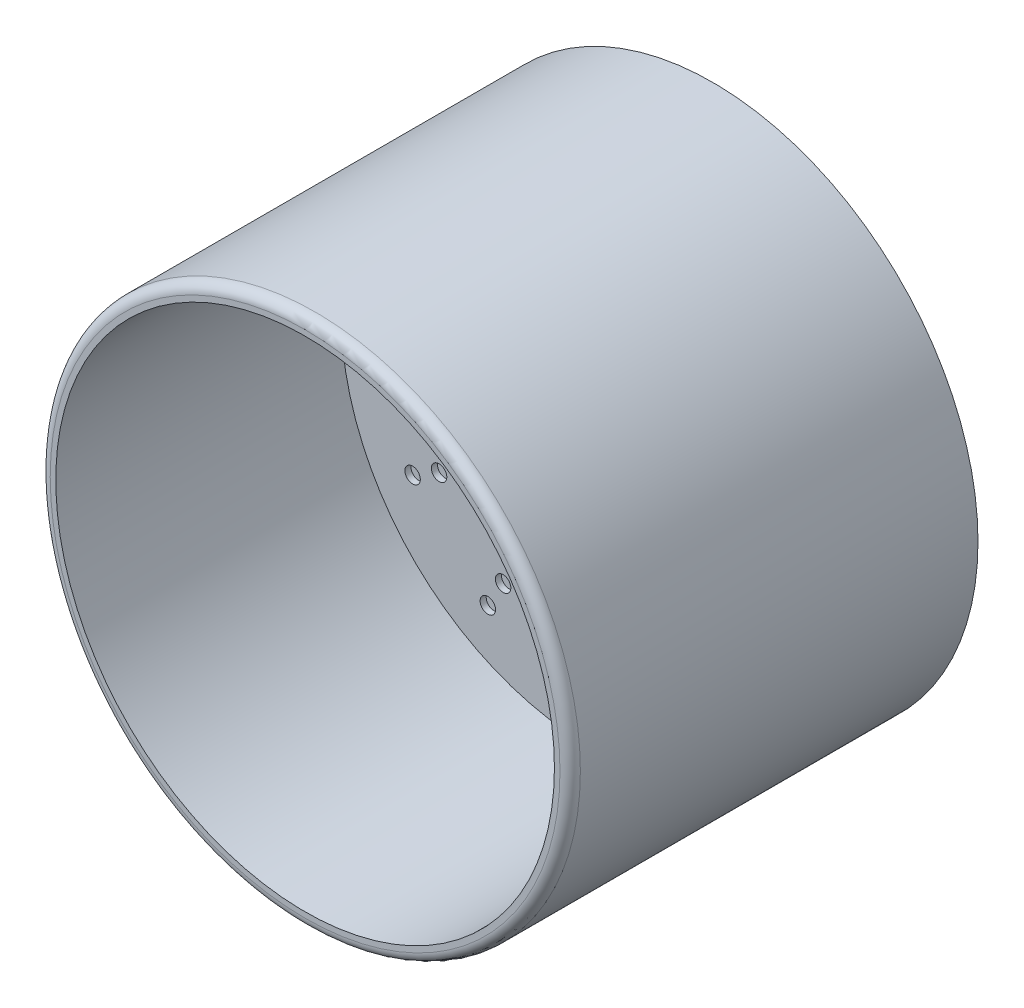
SolidWorks part; units mm, degrees
material "1023 Carbon Steel Sheet (SS)"
ref_plane "Front Plane" through (0, 0, 0) normal (0, 0, 1) x (1, 0, 0)
ref_plane "Top Plane" through (0, 0, 0) normal (0, 1, 0) x (1, 0, 0)
ref_plane "Right Plane" through (0, 0, 0) normal (1, 0, 0) x (0, 0, -1)
sketch "Sketch1" plane through (0, 0, 0) normal (0, 0, 1) x (1, 0, 0)
  circle A0 centre (0, 0) radius 13
extrude "Boss-Extrude1" add sketch "Sketch1" along normal blind 20
sketch "Sketch2" plane through (0, 0, 20) normal (0, 0, 1) x (1, 0, 0)
  circle A0 centre (0, 0) radius 12.2278
extrude "Cut-Extrude1" cut sketch "Sketch2" against normal blind 14
sketch "Sketch3" plane through (0, 0, 6) normal (0, 0, 1) x (1, 0, 0)
  circle A0 centre (0, 10.078) radius 0.3784
  circle A1 centre (0, 8.578) radius 0.3784
  circle A2 centre (0, 7.078) radius 0.3784
  circle A3 centre (0, 5.578) radius 0.3784
  circle A4 centre (0, 4.078) radius 0.3784
  circle A5 centre (0, 2.578) radius 0.3784
  circle A6 centre (5.039, 8.7278) radius 0.3784
  circle A7 centre (4.289, 7.4287) radius 0.3784
  circle A8 centre (3.539, 6.1297) radius 0.3784
  circle A9 centre (2.789, 4.8307) radius 0.3784
  circle A10 centre (2.039, 3.5316) radius 0.3784
  circle A11 centre (1.289, 2.2326) radius 0.3784
  circle A12 centre (8.7278, 5.039) radius 0.3784
  circle A13 centre (7.4287, 4.289) radius 0.3784
  circle A14 centre (6.1297, 3.539) radius 0.3784
  circle A15 centre (4.8307, 2.789) radius 0.3784
  circle A16 centre (3.5316, 2.039) radius 0.3784
  circle A17 centre (2.2326, 1.289) radius 0.3784
  circle A18 centre (10.078, 0) radius 0.3784
  circle A19 centre (8.578, 0) radius 0.3784
  circle A20 centre (7.078, 0) radius 0.3784
  circle A21 centre (5.578, 0) radius 0.3784
  circle A22 centre (4.078, 0) radius 0.3784
  circle A23 centre (2.578, 0) radius 0.3784
  circle A24 centre (8.7278, -5.039) radius 0.3784
  circle A25 centre (7.4287, -4.289) radius 0.3784
  circle A26 centre (6.1297, -3.539) radius 0.3784
  circle A27 centre (4.8307, -2.789) radius 0.3784
  circle A28 centre (3.5316, -2.039) radius 0.3784
  circle A29 centre (2.2326, -1.289) radius 0.3784
  circle A30 centre (5.039, -8.7278) radius 0.3784
  circle A31 centre (4.289, -7.4287) radius 0.3784
  circle A32 centre (3.539, -6.1297) radius 0.3784
  circle A33 centre (2.789, -4.8307) radius 0.3784
  circle A34 centre (2.039, -3.5316) radius 0.3784
  circle A35 centre (1.289, -2.2326) radius 0.3784
  circle A36 centre (0, -10.078) radius 0.3784
  circle A37 centre (0, -8.578) radius 0.3784
  circle A38 centre (0, -7.078) radius 0.3784
  circle A39 centre (0, -5.578) radius 0.3784
  circle A40 centre (0, -4.078) radius 0.3784
  circle A41 centre (0, -2.578) radius 0.3784
  circle A42 centre (-5.039, -8.7278) radius 0.3784
  circle A43 centre (-4.289, -7.4287) radius 0.3784
  circle A44 centre (-3.539, -6.1297) radius 0.3784
  circle A45 centre (-2.789, -4.8307) radius 0.3784
  circle A46 centre (-2.039, -3.5316) radius 0.3784
  circle A47 centre (-1.289, -2.2326) radius 0.3784
  circle A48 centre (-8.7278, -5.039) radius 0.3784
  circle A49 centre (-7.4287, -4.289) radius 0.3784
  circle A50 centre (-6.1297, -3.539) radius 0.3784
  circle A51 centre (-4.8307, -2.789) radius 0.3784
  circle A52 centre (-3.5316, -2.039) radius 0.3784
  circle A53 centre (-2.2326, -1.289) radius 0.3784
  circle A54 centre (-10.078, 0) radius 0.3784
  circle A55 centre (-8.578, 0) radius 0.3784
  circle A56 centre (-7.078, 0) radius 0.3784
  circle A57 centre (-5.578, 0) radius 0.3784
  circle A58 centre (-4.078, 0) radius 0.3784
  circle A59 centre (-2.578, 0) radius 0.3784
  circle A60 centre (-8.7278, 5.039) radius 0.3784
  circle A61 centre (-7.4287, 4.289) radius 0.3784
  circle A62 centre (-6.1297, 3.539) radius 0.3784
  circle A63 centre (-4.8307, 2.789) radius 0.3784
  circle A64 centre (-3.5316, 2.039) radius 0.3784
  circle A65 centre (-2.2326, 1.289) radius 0.3784
  circle A66 centre (-5.039, 8.7278) radius 0.3784
  circle A67 centre (-4.289, 7.4287) radius 0.3784
  circle A68 centre (-3.539, 6.1297) radius 0.3784
  circle A69 centre (-2.789, 4.8307) radius 0.3784
  circle A70 centre (-2.039, 3.5316) radius 0.3784
  circle A71 centre (-1.289, 2.2326) radius 0.3784
  dimension "D1" = 6
  dimension "D2" = 12
extrude "Cut-Extrude2" cut sketch "Sketch3" against normal blind 0.3
fillet "Fillet1" radius 0.5 1 edges at (13, 0, 20)
